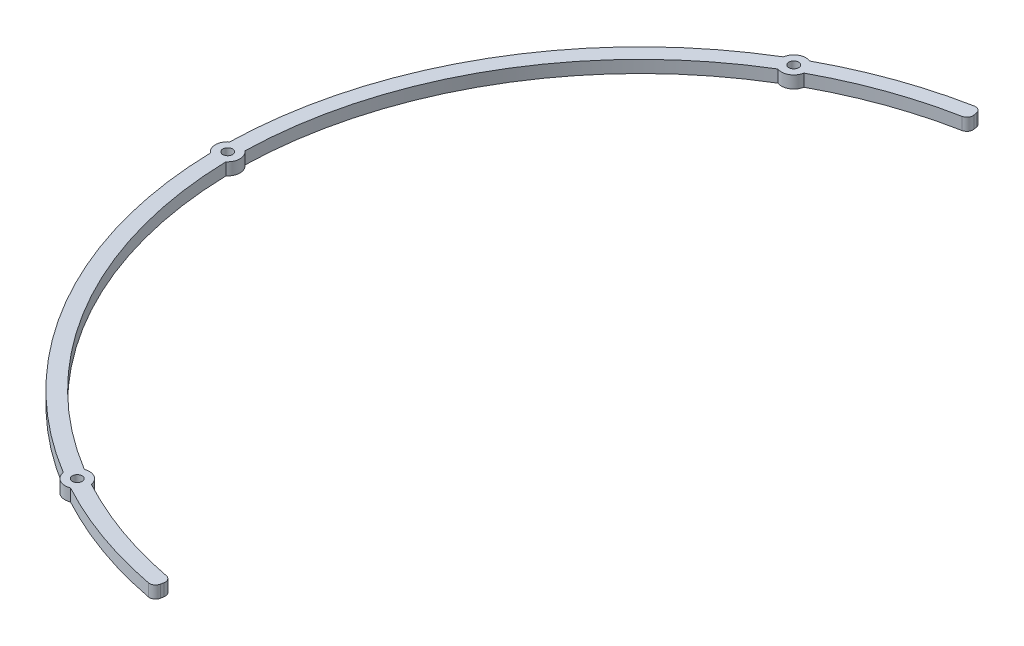
SolidWorks part; units mm, degrees
material "Thornel Mat VMA"
ref_plane "Front Plane" through (0, 0, 0) normal (0, 0, 1) x (1, 0, 0)
ref_plane "Top Plane" through (0, 0, 0) normal (0, 1, 0) x (1, 0, 0)
ref_plane "Right Plane" through (0, 0, 0) normal (1, 0, 0) x (0, 0, -1)
sketch "Sketch1" plane through (0, 0, 0) normal (0, 1, 0) x (1, 0, 0)
  line L0 (0, 0) -> (-23.7898, -134.9187) construction
  line L1 (0, 0) -> (-23.7898, 134.9187) construction
  line L2 (-22.9216, -129.9946) -> (-23.7898, -134.9187)
  line L3 (-23.7898, 134.9187) -> (-22.9216, 129.9946)
  line L4 (0, 0) -> (-137, 0) construction
  arc A0 (-22.9216, 129.9946) -> (-22.9216, -129.9946) centre (0, 0) ccw
  arc A1 (-23.7898, 134.9187) -> (-23.7898, -134.9187) centre (0, 0) ccw
  dimension "D1" = 132
  dimension "D2" = 5
  dimension "D3" = 100
  dimension "D4" = 200
extrude "Boss-Extrude1" add sketch "Sketch1" along normal blind 4 contours A0 L2 A1 L3
fillet "Fillet2" radius 2 4 edges at (-23.7898, 2, -134.9187) (-22.9216, 2, -129.9946) (-22.9216, 2, 129.9946) (-23.7898, 2, 134.9187)
sketch "Sketch2" plane through (0, 4, 0) normal (0, 1, 0) x (1, 0, 0)
  line L0 (-137, 0) -> (-132, 0) construction
  line L1 (-68.0204, 118.9211) -> (-65.5379, 114.5809) construction
  line L2 (0, 0) -> (-68.0204, 118.9211) construction
  line L3 (-137, 0) -> (0, 0) construction
  circle A0 centre (-66.7791, 116.751) radius 1.6
  arc A1 (-25.786, 134.5514) -> (-25.786, -134.5514) centre (0, 0) ccw construction
  arc A2 (-24.8592, 129.638) -> (-24.8592, -129.638) centre (0, 0) ccw construction
  circle A3 centre (-134.5, 0) radius 1.6
  circle A4 centre (-66.7791, -116.751) radius 1.6
  dimension "D1" = 3.2
  dimension "D2" = 3.2
  dimension "D4" = 233.502
extrude "Cut-Extrude1" cut sketch "Sketch2" against normal up to next
sketch "Sketch3" plane through (0, 4, 0) normal (0, 1, 0) x (1, 0, 0)
  circle A0 centre (-66.7791, -116.751) radius 4
  circle A1 centre (-134.5, 0) radius 4
  circle A2 centre (-66.7791, 116.751) radius 4
  circle A3 centre (-66.7791, -116.751) radius 1.6
  circle A4 centre (-134.5, 0) radius 1.6
  circle A5 centre (-66.7791, 116.751) radius 1.6
  dimension "D1" = 8
  dimension "D2" = 8
  dimension "D3" = 8
  dimension "D4" = 3.2
  dimension "D5" = 3.2
  dimension "D6" = 3.2
extrude "Boss-Extrude2" add sketch "Sketch3" against normal up to surface (4 mm away) up to face at (-134.5, 0, 1.6)
